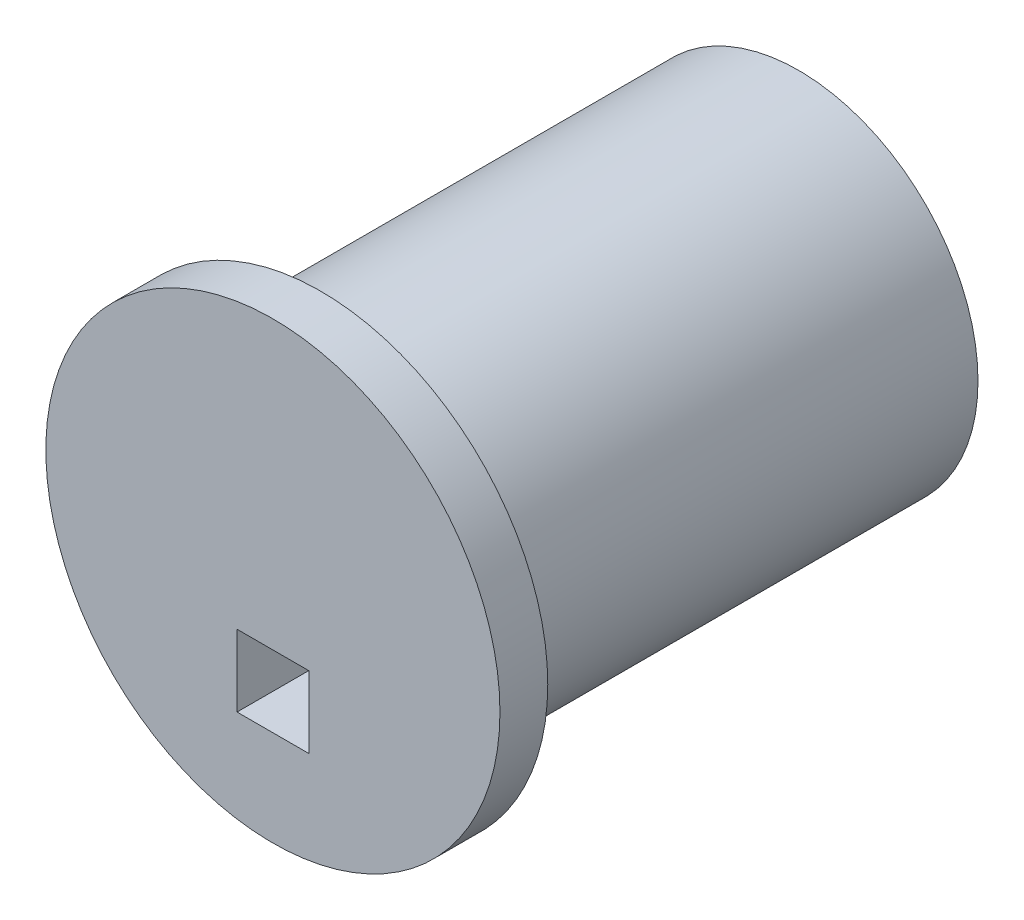
SolidWorks part; units mm, degrees
ref_plane "Front Plane" through (0, 0, 0) normal (0, 0, 1) x (1, 0, 0)
ref_plane "Top Plane" through (0, 0, 0) normal (0, 1, 0) x (1, 0, 0)
ref_plane "Right Plane" through (0, 0, 0) normal (1, 0, 0) x (0, 0, -1)
sketch "Sketch1" plane through (0, 0, 0) normal (0, 0, 1) x (1, 0, 0)
  circle A0 centre (0, 0) radius 7.5
  dimension "D1" = 15
extrude "Boss-Extrude1" add sketch "Sketch1" along normal blind 22
sketch "Sketch4" plane through (0, 0, 22) normal (0, 0, 1) x (1, 0, 0)
  line L1 (-1.5, -5.5) -> (1.5, -5.5)
  line L2 (-1.5, -5.5) -> (-1.5, -2.5)
  line L3 (-1.5, -2.5) -> (1.5, -2.5)
  line L4 (1.5, -5.5) -> (1.5, -2.5)
  line L5 (-1.5, -5.5) -> (1.5, -2.5) construction
  line L6 (-1.5, -2.5) -> (1.5, -5.5) construction
  point P0 (0, -4)
  dimension "D1" = 3
  dimension "D2" = 3
  dimension "D3" = 4
extrude "Cut-Extrude1" cut sketch "Sketch4" against normal blind 10
sketch "Sketch5" plane through (0, 0, 0) normal (0, 0, -1) x (-1, 0, 0)
  circle A0 centre (0, 0) radius 4 construction
  circle A1 centre (0, 4) radius 1.5
  dimension "D1" = 8
  dimension "D2" = 3
extrude "Cut-Extrude2" cut sketch "Sketch5" against normal blind 5
pattern_circular "CirPattern1" count 4 over 360 about axis through (0, 0, 0) along (0, 0, 1) of "Cut-Extrude2"
sketch "Sketch6" plane through (0, 0, 22) normal (0, 0, 1) x (1, 0, 0)
  circle A1 centre (0, 0) radius 7.5 construction
  circle A2 centre (0, 0) radius 7.5
  circle A3 centre (0, 0) radius 9.5
  dimension "D1" = 2
extrude "Boss-Extrude2" add sketch "Sketch6" against normal blind 2
